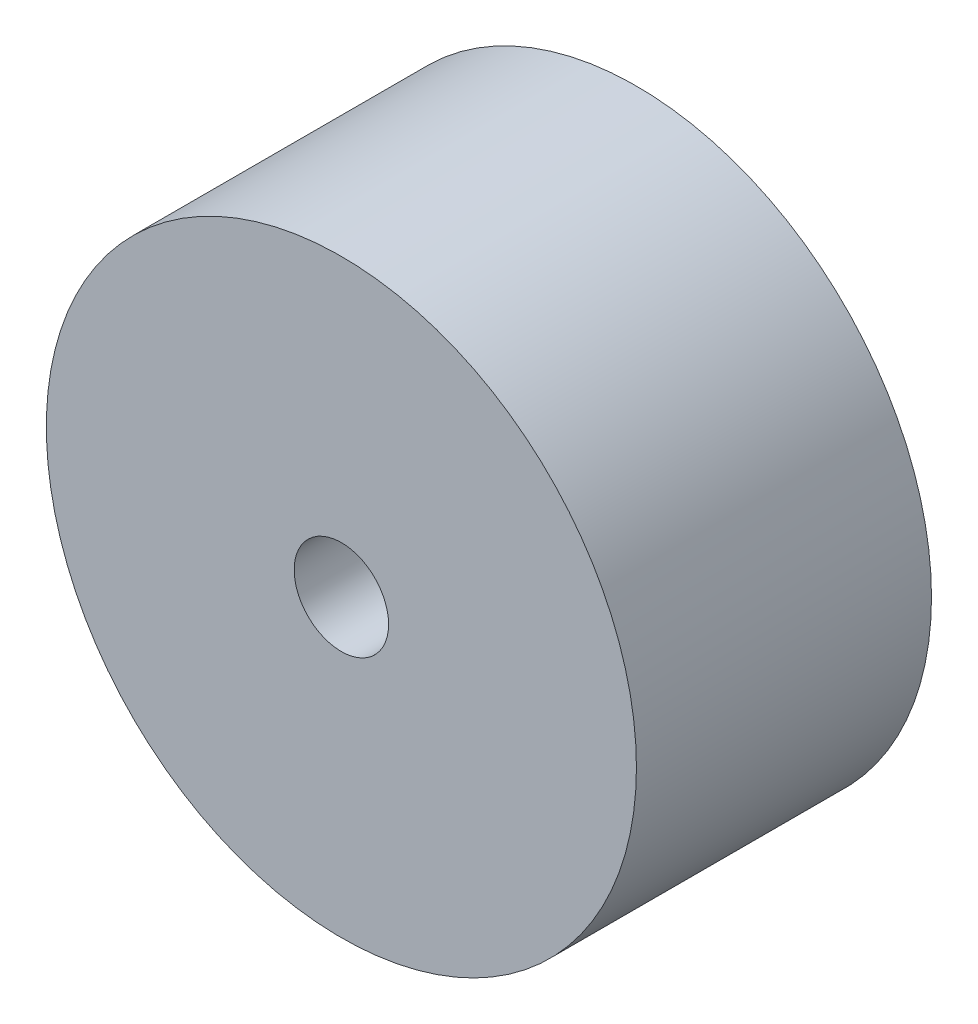
SolidWorks part; units mm, degrees
ref_plane "前视基准面" through (0, 0, 0) normal (0, 0, 1) x (1, 0, 0)
ref_plane "上视基准面" through (0, 0, 0) normal (0, 1, 0) x (1, 0, 0)
ref_plane "右视基准面" through (0, 0, 0) normal (1, 0, 0) x (0, 0, -1)
sketch "草图1" plane through (0, 0, 0) normal (0, 0, 1) x (1, 0, 0)
  circle A0 centre (-1.9288, 3.4132) radius 50
  circle A1 centre (-1.9288, 3.4132) radius 8
  dimension "D1" = 100
  dimension "D2" = 16
extrude "凸台-拉伸1" add sketch "草图1" along normal blind 50
